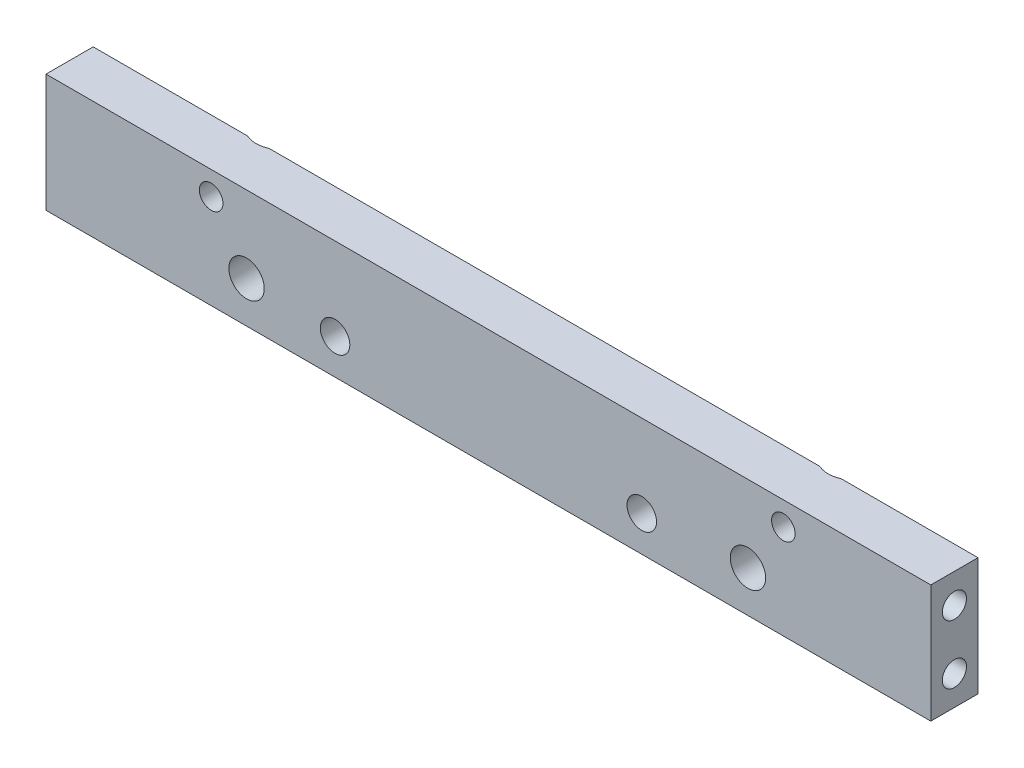
SolidWorks part; units mm, degrees
material "6061 Alloy"
ref_plane "Front Plane" through (0, 0, 0) normal (0, 0, 1) x (1, 0, 0)
ref_plane "Top Plane" through (0, 0, 0) normal (0, 1, 0) x (1, 0, 0)
ref_plane "Right Plane" through (0, 0, 0) normal (1, 0, 0) x (0, 0, -1)
ref_plane "Plane1" through (0, 0, 4) normal (0, 0, 1) x (1, 0, 0)
sketch "Sketch1" plane through (0, 0, 4) normal (0, 0, 1) x (1, 0, 0)
  line L0 (37.5, -5) -> (37.5, 5)
  line L1 (37.5, 5) -> (-37.5, 5)
  line L2 (-37.5, 5) -> (-37.5, -5)
  line L3 (-37.5, -5) -> (37.5, -5)
extrude "Boss-Extrude1" add sketch "Sketch1" against normal blind 4
hole_wizard "M3x0.5 Tapped Hole1" positions "Sketch3" profile "Sketch2" tap size "M3x0.5" standard "ANSI Metric" end condition through all
sketch "Sketch3" plane through (0, 0, 0) normal (0, 0, -1) x (-1, 0, 0)
  point P0 (-13, -2)
  point P1 (13, -2)
sketch "Sketch2" plane through (13, -2, 0) normal (1, 0, 0) x (0, 1, 0)
  line L0 (0, 0) -> (0, 4)
  line L1 (0, 4) -> (1.25, 4)
  line L2 (1.25, 4) -> (1.25, 0)
  line L5 (1.25, 0) -> (0, 0)
  line L11 (0, -6.35) -> (0, 107.95) construction
  dimension "Thread Major Dia." = 2.5
  dimension "Thru Tap Drill Depth" = 4
hole_wizard "CSK for M3 SFHCS1" positions "Sketch5" profile "Sketch4" countersink size "M3" standard "ANSI Metric" end condition through all
sketch "Sketch5" plane through (0, 0, 0) normal (0, 0, -1) x (-1, 0, 0)
  point P0 (-22, -1.5)
  point P1 (20.5, -1.5)
sketch "Sketch4" plane through (22, -1.5, 0) normal (1, 0, 0) x (0, 1, 0)
  line L0 (0, 0) -> (0, 4)
  line L1 (0, 4) -> (1.5, 4)
  line L2 (1.5, 4) -> (1.5, 1.3)
  line L3 (1.5, 1.3) -> (2.8, 0)
  line L5 (2.8, 0) -> (0, 0)
  line L6 (-1.5, 1.3) -> (-2.8, 0) construction
  line L11 (0, -6.35) -> (0, 107.95) construction
  dimension "Thru Hole Dia." = 3
  dimension "Thru Hole Depth" = 4
  dimension "Near C'Sink Dia." = 5.6
  dimension "Near C'Sink Angle" = 90
hole_wizard "CSK for M3 SFHCS2" positions "Sketch7" profile "Sketch6" countersink size "M3" standard "ANSI Metric" end condition through all
sketch "Sketch7" plane through (0, 0, 0) normal (0, 0, -1) x (-1, 0, 0)
  point P0 (23.5, 3)
  point P1 (-25, 3)
sketch "Sketch6" plane through (-23.5, 3, 0) normal (1, 0, 0) x (0, 1, 0)
  line L0 (0, 0) -> (0, 4)
  line L1 (0, 4) -> (1, 4)
  line L2 (1, 4) -> (1, 1.2)
  line L3 (1, 1.2) -> (2.2, 0)
  line L5 (2.2, 0) -> (0, 0)
  line L6 (-1, 1.2) -> (-2.2, 0) construction
  line L11 (0, -6.35) -> (0, 107.95) construction
  dimension "Thru Hole Dia." = 2
  dimension "Thru Hole Depth" = 4
  dimension "Near C'Sink Dia." = 4.4
  dimension "Near C'Sink Angle" = 90
hole_wizard "M2.5x0.45 Tapped Hole1" positions "Sketch9" profile "Sketch8" tap size "M2.5x0.45" standard "ANSI Metric"
sketch "Sketch9" plane through (37.5, 0, 0) normal (1, 0, 0) x (0, 0, -1)
  point P0 (-2, 2.5)
  point P1 (-2, -2.5)
sketch "Sketch8" plane through (37.5, 2.5, 2) normal (0, 1, 0) x (0, 0, -1)
  line L0 (0, 0) -> (0, 6.9659)
  line L1 (0, 6.9659) -> (1.025, 6.35)
  line L2 (1.025, 6.35) -> (1.025, 0)
  line L5 (1.025, 0) -> (0, 0)
  line L10 (0, 6.9659) -> (-1.025, 6.35) construction
  line L11 (0, -6.35) -> (0, 107.95) construction
  dimension "Tap Drill Dia." = 2.05
  dimension "Tap Drill Depth" = 6.35
  dimension "Drill Angle" = 118
hole_wizard "M2.5x0.45 Tapped Hole2" positions "Sketch11" profile "Sketch10" tap size "M2.5x0.45" standard "ANSI Metric"
sketch "Sketch11" plane through (-37.5, 0, 0) normal (-1, 0, 0) x (0, 0, 1)
  point P0 (2, -2.5)
  point P1 (2, 2.5)
sketch "Sketch10" plane through (-37.5, -2.5, 2) normal (0, 1, 0) x (0, 0, 1)
  line L0 (0, 0) -> (0, 6.9659)
  line L1 (0, 6.9659) -> (1.025, 6.35)
  line L2 (1.025, 6.35) -> (1.025, 0)
  line L5 (1.025, 0) -> (0, 0)
  line L10 (0, 6.9659) -> (-1.025, 6.35) construction
  line L11 (0, -6.35) -> (0, 107.95) construction
  dimension "Tap Drill Dia." = 2.05
  dimension "Tap Drill Depth" = 6.35
  dimension "Drill Angle" = 118
